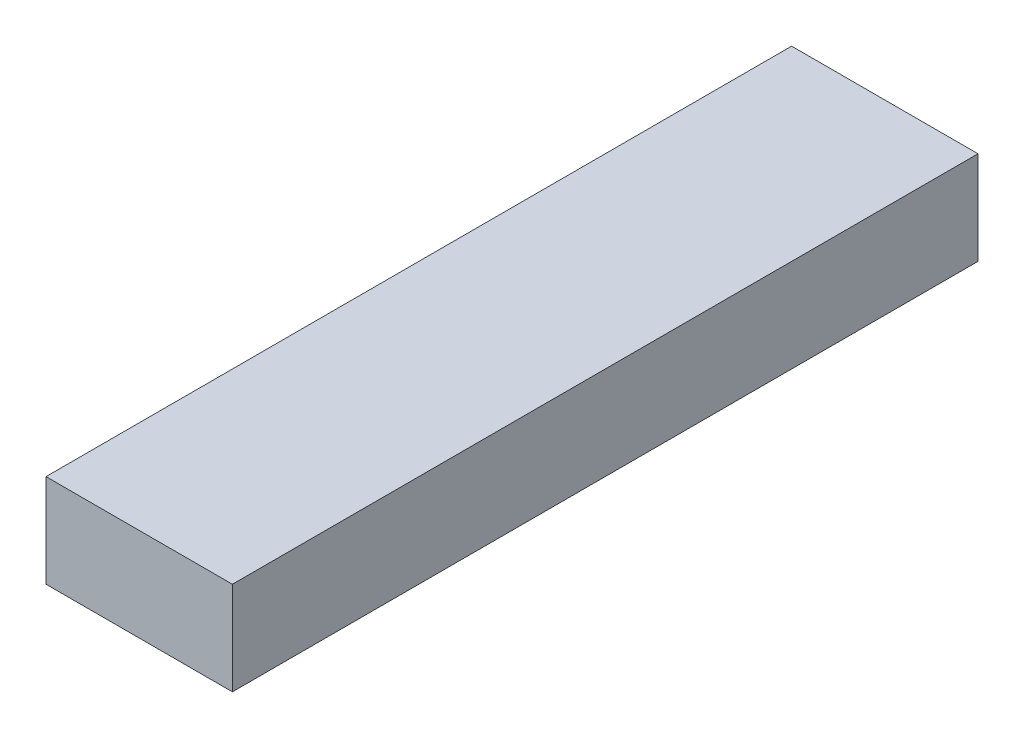
SolidWorks part; units mm, degrees
ref_plane "前视基准面" through (0, 0, 0) normal (0, 0, 1) x (1, 0, 0)
ref_plane "上视基准面" through (0, 0, 0) normal (0, 1, 0) x (1, 0, 0)
ref_plane "右视基准面" through (0, 0, 0) normal (1, 0, 0) x (0, 0, -1)
other "Configuration Table"
sketch "Profile1" plane through (0, 0, 0) normal (0, 0, 1) x (1, 0, 0)
  line L1 (-5, -2.5) -> (5, -2.5)
  line L2 (-5, -2.5) -> (-5, 2.5)
  line L3 (-5, 2.5) -> (5, 2.5)
  line L4 (5, -2.5) -> (5, 2.5)
sketch "Path1" plane through (0, 0, 0) normal (1, 0, 0) x (0, 0, -1)
  line L0 (0, 0) -> (-40, 0)
sweep "modern_sweep_rect_baseline" add profiles "Profile1" path "Path1"
